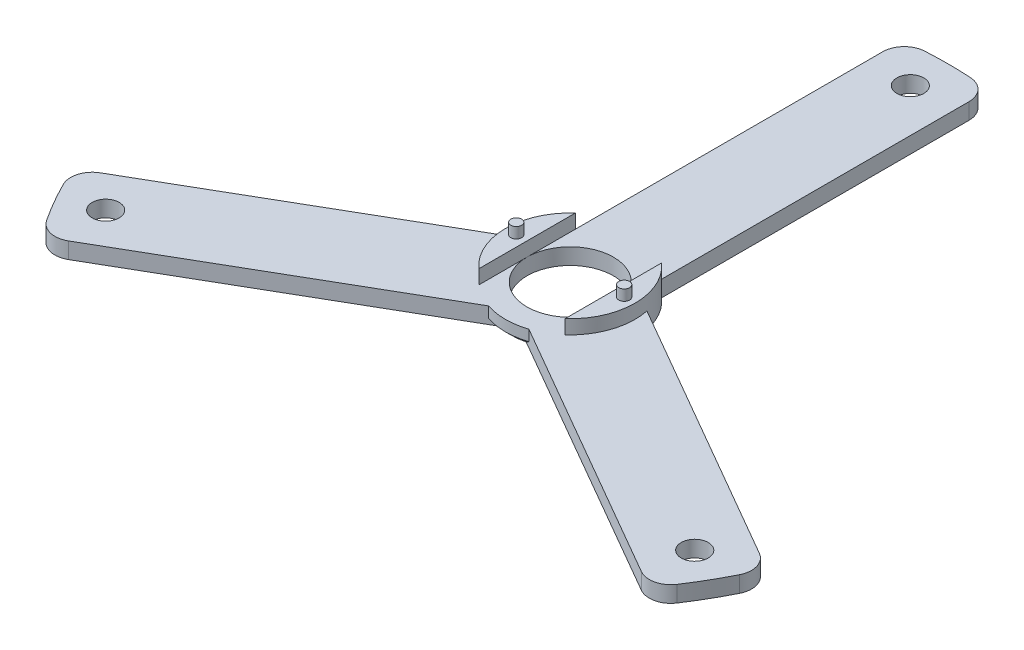
SolidWorks part; units mm, degrees
material "6061-T6 铝合金"
ref_plane "前视基准面" through (0, 0, 0) normal (0, 0, 1) x (1, 0, 0)
ref_plane "上视基准面" through (0, 0, 0) normal (0, 1, 0) x (1, 0, 0)
ref_plane "右视基准面" through (0, 0, 0) normal (1, 0, 0) x (0, 0, -1)
sketch "草图1" plane through (0, 0, 0) normal (0, 1, 0) x (1, 0, 0)
  line L0 (0, 0) -> (0, 35) construction
  line L1 (4, 4.4721) -> (4, 34.7707)
  line L2 (-4, 4.4721) -> (-4, 34.7707)
  line L3 (5.873, 1.228) -> (32.1123, -13.9212)
  line L4 (1.873, -5.7002) -> (28.1123, -20.8494)
  line L5 (-1.873, -5.7002) -> (-28.1123, -20.8494)
  line L6 (-5.873, 1.228) -> (-32.1123, -13.9212)
  arc A0 (-32.1123, -13.9212) -> (-28.1123, -20.8494) centre (0, 0) ccw
  arc A1 (-4, 4.4721) -> (-5.873, 1.228) centre (0, 0) ccw
  arc A2 (4, 34.7707) -> (-4, 34.7707) centre (0, 0) ccw
  arc A3 (28.1123, -20.8494) -> (32.1123, -13.9212) centre (0, 0) ccw
  arc A4 (5.873, 1.228) -> (4, 4.4721) centre (0, 0) ccw
  arc A5 (-1.873, -5.7002) -> (1.873, -5.7002) centre (0, 0) ccw
  point P19 (0, 0)
  dimension "D1" = 70
  dimension "D2" = 12
  dimension "D3" = 8
  dimension "D4" = 3
extrude "凸台-拉伸1" add sketch "草图1" along normal blind 1.5
fillet "圆角1" radius 2 6 edges at (-4, 0.75, -34.7707) (4, 0.75, -34.7707) (32.1123, 0.75, 13.9212) (28.1123, 0.75, 20.8494) (-32.1123, 0.75, 13.9212) (-28.1123, 0.75, 20.8494)
sketch "草图2" plane through (0, 1.5, 0) normal (0, 1, 0) x (1, 0, 0)
  line L0 (0, 0) -> (0, 31.5) construction
  circle A0 centre (0, 31.5) radius 1.25
  circle A1 centre (27.2798, -15.75) radius 1.25
  circle A2 centre (-27.2798, -15.75) radius 1.25
  dimension "D2" = 2.5
  dimension "D1" = 31.5
  dimension "D3" = 3
extrude "切除-拉伸1" cut sketch "草图2" against normal through all both and the other way through all
sketch "草图4" plane through (0, 1.5, 0) normal (0, 1, 0) x (1, 0, 0)
  line L0 (-4, 4.4721) -> (-4, -4.4721)
  line L2 (0, 0) -> (0, 4.927) construction
  line L3 (4, 4.4721) -> (4, -4.4721)
  line L4 (-4, 32.9393) -> (-4, 4.4721) construction
  arc A0 (-4, 4.4721) -> (-4, -4.4721) centre (0, 0) ccw
  arc A1 (4, -4.4721) -> (4, 4.4721) centre (0, 0) ccw
  dimension "D1" = 6
extrude "凸台-拉伸2" add sketch "草图4" along normal blind 1.3
sketch "草图5" plane through (0, 2.8, 0) normal (0, 1, 0) x (1, 0, 0)
  line L0 (0, 0) -> (0, 10.1544) construction
  circle A0 centre (5, 0) radius 0.5
  circle A1 centre (-5, 0) radius 0.5
  dimension "D2" = 1
  dimension "D1" = 10
extrude "凸台-拉伸3" add sketch "草图5" along normal blind 1
sketch "草图6" plane through (0, 1.5, 0) normal (0, 1, 0) x (1, 0, 0)
  circle A0 centre (0, 0) radius 4
extrude "切除-拉伸2" cut sketch "草图6" against normal through all both and the other way through all
chamfer "倒角1" distance 0.5 angle 45 1 edges at (0, 0, 6)
